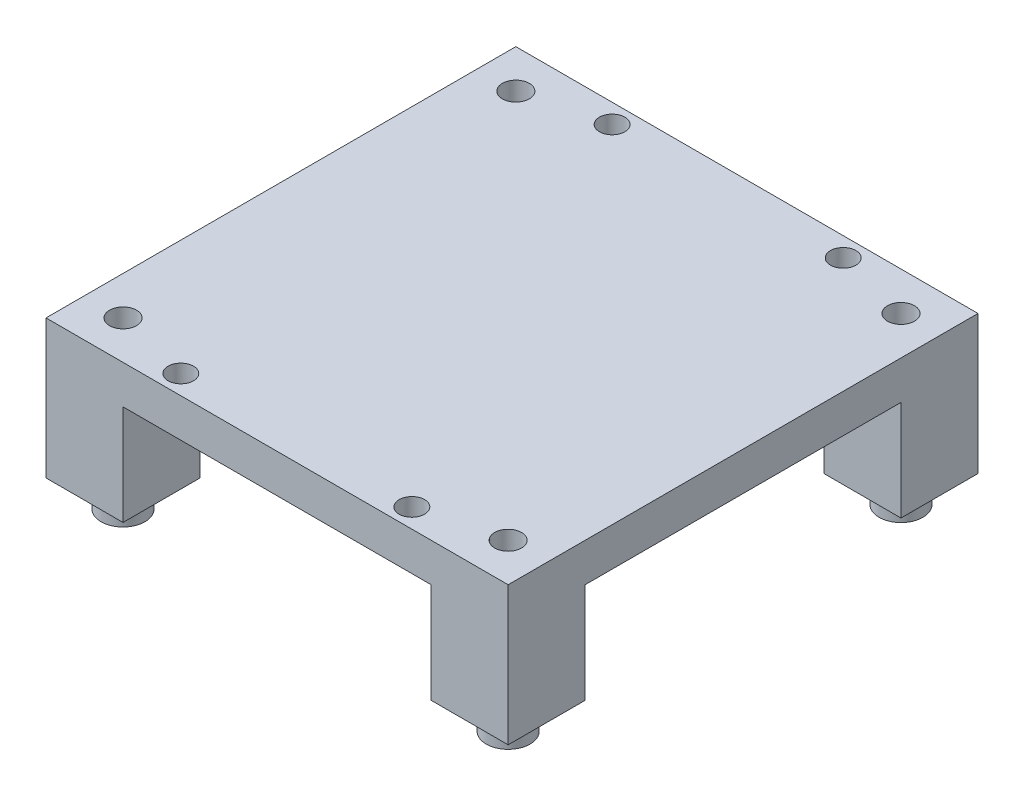
SolidWorks part; units mm, degrees
material "1100-H12 棒材(SS)"
ref_plane "前视基准面" through (0, 0, 0) normal (0, 0, 1) x (1, 0, 0)
ref_plane "上视基准面" through (0, 0, 0) normal (0, 1, 0) x (1, 0, 0)
ref_plane "右视基准面" through (0, 0, 0) normal (1, 0, 0) x (0, 0, -1)
sketch "草图1" plane through (0, 0, 0) normal (0, 1, 0) x (1, 0, 0)
  line L1 (0, 0) -> (60, 0)
  line L2 (0, 0) -> (0, 61)
  line L3 (0, 61) -> (60, 61)
  line L4 (60, 0) -> (60, 61)
  dimension "D1" = 61
  dimension "D2" = 60
extrude "凸台-拉伸1" add sketch "草图1" along normal blind 5
sketch "草图2" plane through (0, 0, 0) normal (0, -1, 0) x (1, 0, 0)
  line L1 (0, 0) -> (10, 0)
  line L2 (0, 0) -> (0, -10)
  line L3 (0, -10) -> (10, -10)
  line L4 (10, 0) -> (10, -10)
  line L5 (60, 0) -> (50, 0)
  line L6 (60, 0) -> (60, -10)
  line L7 (60, -10) -> (50, -10)
  line L8 (50, 0) -> (50, -10)
  line L9 (60, -61) -> (50, -61)
  line L10 (60, -61) -> (60, -51)
  line L11 (60, -51) -> (50, -51)
  line L12 (50, -61) -> (50, -51)
  line L13 (0, -61) -> (10, -61)
  line L14 (0, -61) -> (0, -51)
  line L15 (0, -51) -> (10, -51)
  line L16 (10, -61) -> (10, -51)
  dimension "D1" = 10
  dimension "D2" = 10
  dimension "D3" = 10
  dimension "D4" = 10
  dimension "D5" = 10
  dimension "D6" = 10
  dimension "D7" = 10
  dimension "D8" = 10
extrude "凸台-拉伸2" add sketch "草图2" along normal blind 13
sketch "草图3" plane through (0, -13, 0) normal (0, -1, 0) x (1, 0, 0)
  line L0 (0, -10) -> (10, 0)
  line L1 (50, 0) -> (60, -10)
  line L2 (10, -61) -> (0, -51)
  line L3 (50, -61) -> (60, -51)
sketch "草图4" plane through (0, -13, 0) normal (0, -1, 0) x (-1, 0, 0)
  line L0 (0, 10) -> (-10, 0) construction
  line L1 (-10, 61) -> (0, 51) construction
  line L2 (-50, 61) -> (-60, 51) construction
  line L3 (-50, 0) -> (-60, 10) construction
  point P0 (-5, 5)
  point P4 (-5, 56)
  point P8 (-55, 56)
  point P12 (-55, 5)
sketch "草图6" plane through (0, 5, 0) normal (0, 1, 0) x (1, 0, 0)
  line L0 (60, 61) -> (0, 61) construction
  line L1 (12.5, 61) -> (47.5, 61)
  line L2 (12.5, 61) -> (12.5, 0)
  line L3 (12.5, 0) -> (47.5, 0)
  line L4 (47.5, 61) -> (47.5, 0)
  line L5 (0, 0) -> (60, 0) construction
  line L6 (60, 0) -> (60, 61) construction
  line L7 (12.5, 61) -> (47.5, 0)
  line L9 (15, 2.5) -> (45, 2.5)
  line L10 (15, 2.5) -> (15, 58.5)
  line L11 (15, 58.5) -> (45, 58.5)
  line L12 (45, 2.5) -> (45, 58.5)
  line L13 (15, 2.5) -> (45, 58.5) construction
  line L14 (15, 58.5) -> (45, 2.5) construction
  point P10 (30, 30.5)
  dimension "D1" = 35
  dimension "D2" = 12.5
  dimension "D3" = 30
  dimension "D4" = 56
sketch "草图7" plane through (0, 5, 0) normal (0, 1, 0) x (1, 0, 0)
  point P0 (15, 58.5)
  point P3 (45, 58.5)
  point P6 (45, 2.5)
  point P9 (15, 2.5)
hole_wizard "孔2" positions "草图7" profile "草图8" legacy end condition through all
sketch "草图8" plane through (15, 5, -58.5) normal (1, 0, 0) x (0, 0, 1)
  line L0 (0, 0) -> (0, 18)
  line L1 (0, 18) -> (1.65, 18)
  line L2 (1.65, 18) -> (1.65, 0)
  line L3 (1.65, 0) -> (0, 0)
  line L4 (0, 110) -> (0, -10) construction
  dimension "直径" = 3.3
  dimension "深度" = 18
sketch "草图9" plane through (0, -13, 0) normal (0, -1, 0) x (1, 0, 0)
  line L0 (10, -61) -> (0, -51) construction
  line L1 (50, -61) -> (60, -51) construction
  line L2 (50, 0) -> (60, -10) construction
  line L3 (0, -10) -> (10, 0) construction
  circle A0 centre (5, -56) radius 2.85
  circle A1 centre (55, -56) radius 2.85
  circle A2 centre (55, -5) radius 2.85
  circle A3 centre (5, -5) radius 2.85
  dimension "D1" = 5.7
  dimension "D2" = 5.7
  dimension "D3" = 5.7
  dimension "D4" = 5.7
extrude "凸台-拉伸3" add sketch "草图9" along normal blind 3.5
hole_wizard "孔1" positions "草图4" profile "草图5" legacy
sketch "草图5" plane through (5, -13, -5) normal (1, 0, 0) x (0, 0, -1)
  line L0 (0, 0) -> (0, 18)
  line L1 (0, 18) -> (1.75, 18)
  line L2 (1.75, 18) -> (1.75, 0)
  line L3 (1.75, 0) -> (0, 0)
  line L4 (0, 110) -> (0, -10) construction
  dimension "直径" = 3.5
  dimension "深度" = 18
hole_wizard "孔3" positions "草图10" profile "草图11" legacy end condition through all
sketch "草图10" plane through (0, -16.5, 0) normal (0, -1, 0) x (-1, 0, 0)
  line L0 (0, 10) -> (-10, 0) construction
  line L1 (-10, 61) -> (0, 51) construction
  line L2 (-50, 61) -> (-60, 51) construction
  line L3 (-50, 0) -> (-60, 10) construction
  point P0 (-5, 5)
  point P4 (-5, 56)
  point P8 (-55, 56)
  point P12 (-55, 5)
sketch "草图11" plane through (5, -16.5, -5) normal (1, 0, 0) x (0, 0, -1)
  line L0 (0, 0) -> (0, 21.5)
  line L1 (0, 21.5) -> (1.75, 21.5)
  line L2 (1.75, 21.5) -> (1.75, 0)
  line L3 (1.75, 0) -> (0, 0)
  line L4 (0, 110) -> (0, -10) construction
  dimension "直径" = 3.5
  dimension "深度" = 21.5
